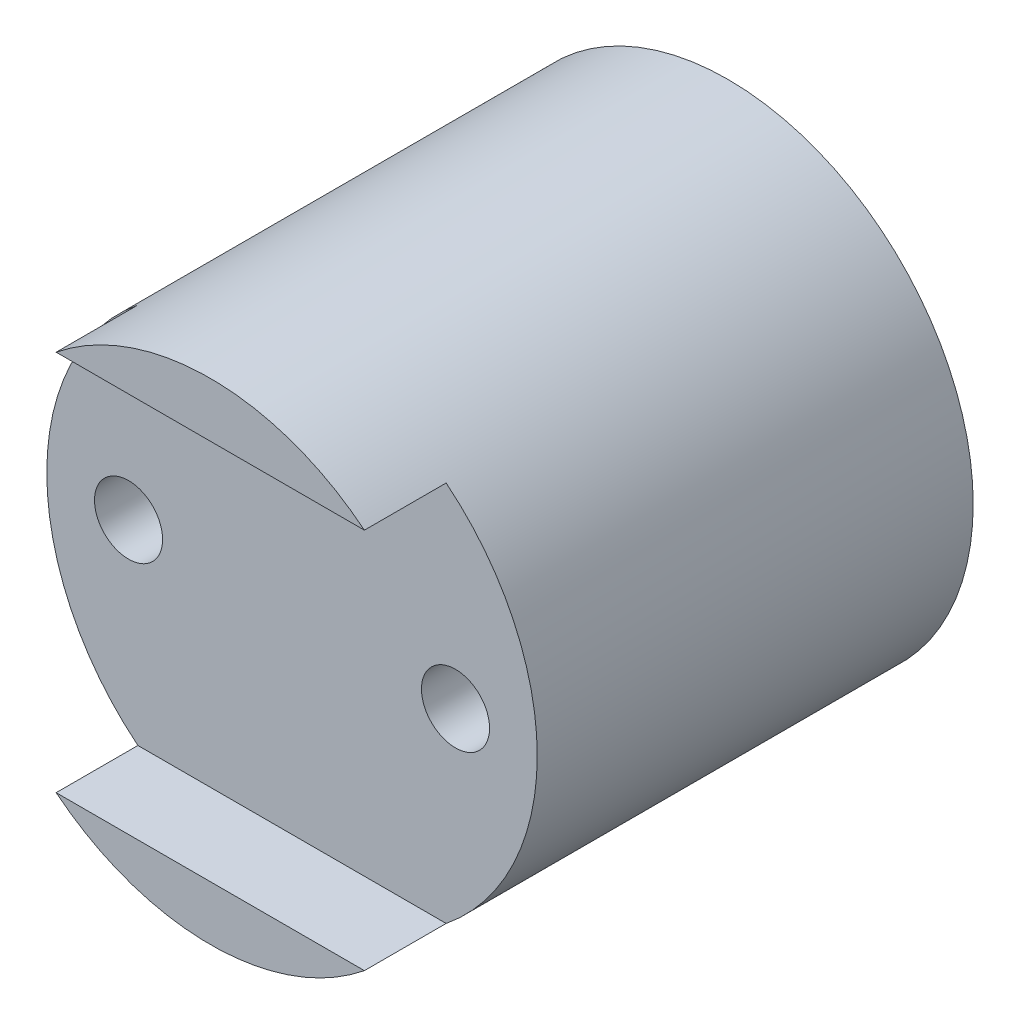
SolidWorks part; units mm, degrees
ref_plane "Front Plane" through (0, 0, 0) normal (0, 0, 1) x (1, 0, 0)
ref_plane "Top Plane" through (0, 0, 0) normal (0, 1, 0) x (1, 0, 0)
ref_plane "Right Plane" through (0, 0, 0) normal (1, 0, 0) x (0, 0, -1)
sketch "Sketch1" plane through (0, 0, 0) normal (0, 0, 1) x (1, 0, 0)
  circle A0 centre (0, 0) radius 9
extrude "Body" add sketch "Sketch1" along normal blind 19
sketch "Sketch2" plane through (0, 0, 0) normal (0, 0, 1) x (1, 0, 0)
  circle A0 centre (0, 0) radius 4
extrude "Bore" cut sketch "Sketch2" along normal blind 12
sketch "Sketch3" plane through (0, 0, 0) normal (0, 0, 1) x (1, 0, 0)
  line L1 (3.2, -4.5) -> (4.7, -4.5)
  line L2 (3.2, -4.5) -> (3.2, 4.5)
  line L3 (3.2, 4.5) -> (4.7, 4.5)
  line L4 (4.7, -4.5) -> (4.7, 4.5)
extrude "Bore_flat" add sketch "Sketch3" along normal blind 12
ref_plane "Plane_z12" through (0, 0, 12) normal (0, 0, 1) x (1, 0, 0)
sketch "Sketch4" plane through (0, 0, 12) normal (0, 0, 1) x (1, 0, 0)
  circle A0 centre (0, 0) radius 3
extrude "Magnet_pocket" cut sketch "Sketch4" along normal blind 3
ref_plane "Plane_z16" through (0, 0, 16) normal (0, 0, 1) x (1, 0, 0)
sketch "Sketch5" plane through (0, 0, 16) normal (0, 0, 1) x (1, 0, 0)
  line L1 (-11, -7) -> (11, -7)
  line L2 (-11, -7) -> (-11, 7)
  line L3 (-11, 7) -> (11, 7)
  line L4 (11, -7) -> (11, 7)
extrude "Arm_slot" cut sketch "Sketch5" along normal blind 3
ref_plane "Plane_z10" through (0, 0, 10) normal (0, 0, 1) x (1, 0, 0)
sketch "Sketch6" plane through (0, 0, 10) normal (0, 0, 1) x (1, 0, 0)
  circle A0 centre (-6, 0) radius 1.25
  circle A1 centre (6, 0) radius 1.25
extrude "Arm_screws" cut sketch "Sketch6" along normal blind 6
